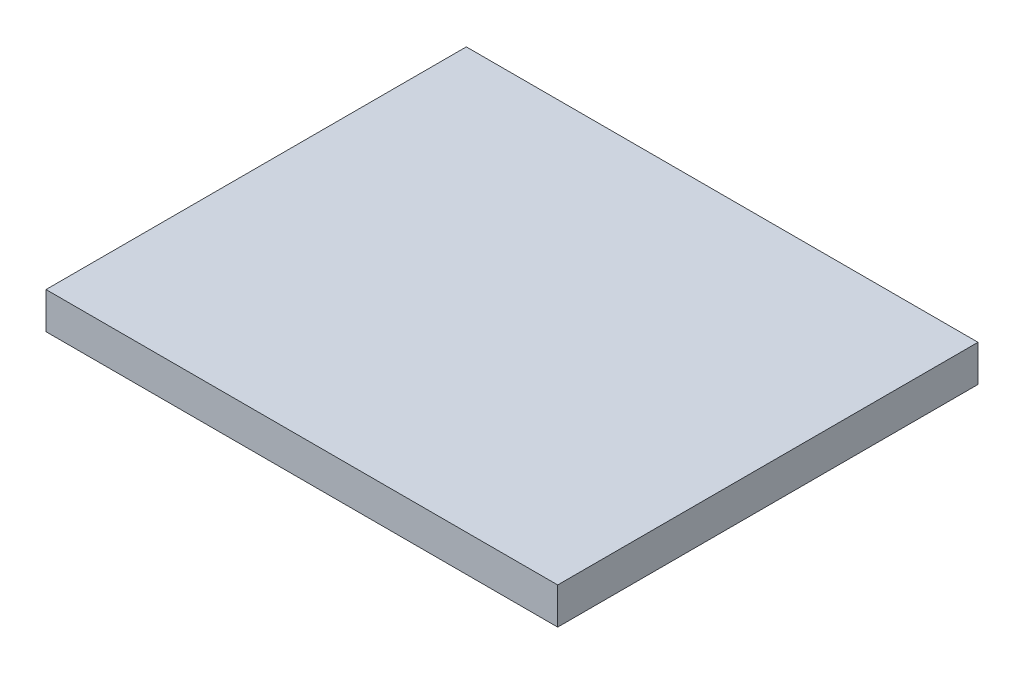
SolidWorks part; units mm, degrees
ref_plane "Front Plane" through (0, 0, 0) normal (0, 0, 1) x (1, 0, 0)
ref_plane "Top Plane" through (0, 0, 0) normal (0, 1, 0) x (1, 0, 0)
ref_plane "Right Plane" through (0, 0, 0) normal (1, 0, 0) x (0, 0, -1)
sketch "Sketch1" plane through (0, 0, 0) normal (0, 1, 0) x (1, 0, 0)
  line L1 (-70, -57.5) -> (70, -57.5)
  line L2 (-70, -57.5) -> (-70, 57.5)
  line L3 (-70, 57.5) -> (70, 57.5)
  line L4 (70, -57.5) -> (70, 57.5)
extrude "Boss-Extrude1" add sketch "Sketch1" along normal blind 10
